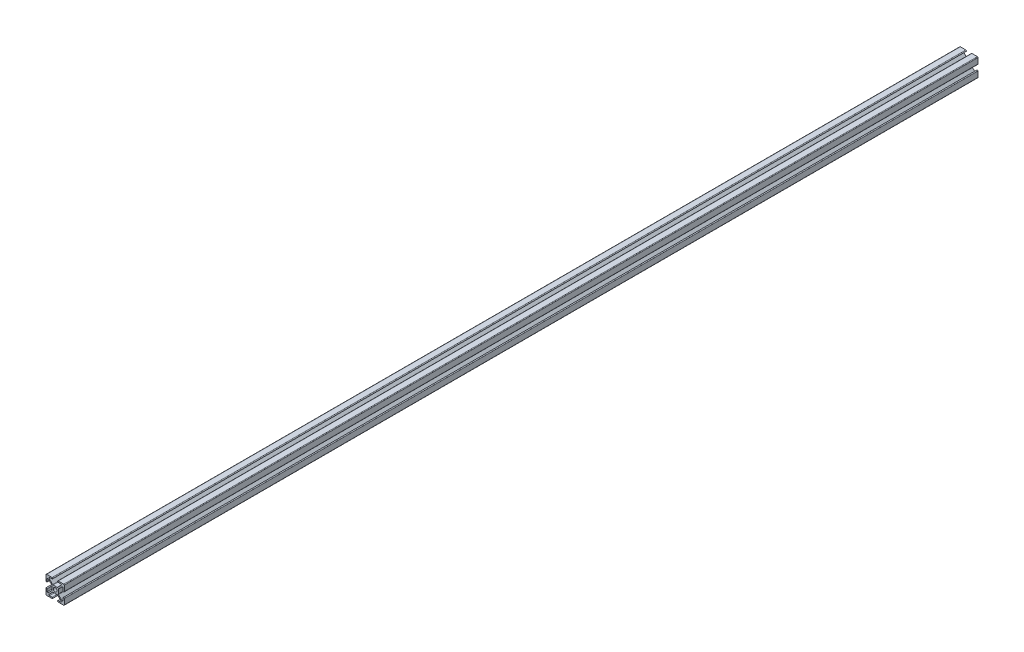
SolidWorks part; units mm, degrees
ref_plane "Alzado" through (0, 0, 0) normal (0, 0, 1) x (1, 0, 0)
ref_plane "Planta" through (0, 0, 0) normal (0, 1, 0) x (1, 0, 0)
ref_plane "Vista lateral" through (0, 0, 0) normal (1, 0, 0) x (0, 0, -1)
sketch "Croquis1" plane through (0, 0, 0) normal (0, 0, 1) x (1, 0, 0)
  line L1 (-14, 15) -> (14, 15)
  line L2 (-15, 14) -> (-15, -14)
  line L3 (-14, -15) -> (14, -15)
  line L4 (15, 14) -> (15, -14)
  line L5 (-15, 15) -> (15, -15) construction
  line L6 (-15, -15) -> (15, 15) construction
  arc A0 (-14, 15) -> (-15, 14) centre (-14, 14) ccw
  arc A1 (14, -15) -> (15, -14) centre (14, -14) ccw
  arc A2 (-14, -15) -> (-15, -14) centre (-14, -14) cw
  arc A3 (15, 14) -> (14, 15) centre (14, 14) ccw
  point P0 (0, 0)
  dimension "D3" = 1
  dimension "D4" = 1
  dimension "D1" = 30
  dimension "D2" = 30
extrude "Saliente-Extruir1" add sketch "Croquis1" against normal blind 1500
sketch "Croquis2" plane through (0, 0, 0) normal (0, 0, 1) x (1, 0, 0)
  circle A0 centre (0, 0) radius 3
  dimension "D1" = 6
sketch "Croquis3" plane through (0, 0, 0) normal (0, 0, 1) x (1, 0, 0)
  line L0 (-15, 0) -> (15, 0) construction
  line L1 (4.0787, -5.4929) -> (9.8787, -11.2929)
  line L2 (-11.2929, 9.8787) -> (-5.4929, 4.0787)
  line L3 (-9.8787, 11.2929) -> (-4.0787, 5.4929)
  line L4 (-13, 9.1716) -> (-13, 5)
  line L5 (-15, 14) -> (-15, -14) construction
  line L6 (-5.2, 3.3716) -> (-5.2, -3.3716)
  line L7 (-9.1716, 13) -> (-5, 13)
  line L8 (9.8787, 11.2929) -> (4.0787, 5.4929)
  line L9 (11.2929, 9.8787) -> (5.4929, 4.0787)
  line L10 (-3.3716, 5.2) -> (3.3716, 5.2)
  line L11 (14, 15) -> (-14, 15) construction
  line L12 (13, 9.1716) -> (13, 5)
  line L13 (5.2, 3.3716) -> (5.2, -3.3716)
  line L14 (15, -14) -> (15, 14) construction
  line L15 (-9.1716, -13) -> (-5, -13)
  line L16 (-3.3716, -5.2) -> (3.3716, -5.2)
  line L17 (-14, -15) -> (14, -15) construction
  line L18 (-5.4929, -4.0787) -> (-11.2929, -9.8787)
  line L19 (5.4929, -4.0787) -> (11.2929, -9.8787)
  line L20 (-4.0787, -5.4929) -> (-9.8787, -11.2929)
  line L21 (5, -13) -> (9.1716, -13)
  line L22 (-13, -5) -> (-13, -9.1716)
  line L23 (13, -5) -> (13, -9.1716)
  line L24 (0, 15) -> (0, -5.2) construction
  line L34 (5, 13) -> (9.1716, 13)
  arc A0 (9.8787, 11.2929) -> (9.1716, 13) centre (9.1716, 12) ccw
  arc A1 (-9.8787, 11.2929) -> (-9.1716, 13) centre (-9.1716, 12) cw
  arc A2 (9.8787, 11.2929) -> (9.1716, 13) centre (9.1716, 12) ccw
  arc A3 (13, 9.1716) -> (11.2929, 9.8787) centre (12, 9.1716) ccw
  arc A4 (11.2929, -9.8787) -> (13, -9.1716) centre (12, -9.1716) ccw
  arc A5 (9.1716, -13) -> (9.8787, -11.2929) centre (9.1716, -12) ccw
  arc A6 (-9.1716, -13) -> (-9.8787, -11.2929) centre (-9.1716, -12) cw
  arc A7 (-11.2929, -9.8787) -> (-13, -9.1716) centre (-12, -9.1716) cw
  arc A8 (-13, 9.1716) -> (-11.2929, 9.8787) centre (-12, 9.1716) cw
  arc A9 (-4.0787, -5.4929) -> (-3.3716, -5.2) centre (-3.3716, -6.2) cw
  arc A10 (3.3716, -5.2) -> (4.0787, -5.4929) centre (3.3716, -6.2) cw
  arc A11 (5.4929, -4.0787) -> (5.2, -3.3716) centre (6.2, -3.3716) cw
  arc A12 (5.2, 3.3716) -> (5.4929, 4.0787) centre (6.2, 3.3716) cw
  arc A13 (3.3716, 5.2) -> (4.0787, 5.4929) centre (3.3716, 6.2) ccw
  arc A14 (-3.3716, 5.2) -> (-4.0787, 5.4929) centre (-3.3716, 6.2) cw
  arc A15 (-5.4929, -4.0787) -> (-5.2, -3.3716) centre (-6.2, -3.3716) ccw
  arc A16 (-5.2, 3.3716) -> (-5.4929, 4.0787) centre (-6.2, 3.3716) ccw
  circle A17 centre (-14, -5) radius 1
  circle A18 centre (-14, 5) radius 1
  circle A19 centre (-5, -14) radius 1
  circle A20 centre (5, -14) radius 1
  circle A21 centre (14, 5) radius 1
  circle A22 centre (14, -5) radius 1
  circle A23 centre (-5, 14) radius 1
  circle A24 centre (5, 14) radius 1
  point P20 (-11.5858, -13)
  point P30 (-13, -11.5858)
  point P43 (-3.7858, -5.2)
  point P50 (3.7858, -5.2)
  point P53 (5.2, -3.7858)
  point P62 (-5.2, -3.7858)
  line M2 (-15, 14) -> (-15, -14)
  line M4 (-14, -15) -> (14, -15)
  line M6 (15, -14) -> (15, 14)
  line M8 (14, 15) -> (-14, 15)
  dimension "D6" = 9.8
  dimension "D7" = 2
  dimension "D12" = 2
  dimension "D19" = 1
  dimension "D2" = 1
  dimension "D3" = 1
  dimension "D4" = 1
  dimension "D16" = 1
  dimension "D5" = 2
  dimension "D8" = 9.8
  dimension "D9" = 2
  dimension "D10" = 9.8
  dimension "D11" = 9.8
  dimension "D15" = 1
  dimension "D20" = 1
  dimension "D23" = 1
  dimension "D24" = 1
  dimension "D27" = 1
  dimension "D28" = 1
extrude "Cortar-Extruir1" cut sketch "Croquis2" against normal through all
extrude "Cortar-Extruir3" cut sketch "Croquis3" against normal through all contours A18 A17 L22 A7 L18 A15 L6 A16 L2 A8 L4 M2 | A24 A23 L7 A1 L3 A14 L10 A13 L8 A0 L34 M8 | A20 L21 A5 L1 A10 L16 A9 L20 A6 L15 A19 M4 | A22 A21 L12 A3 L9 A12 L13 A11 L19 A4 L23 M6
